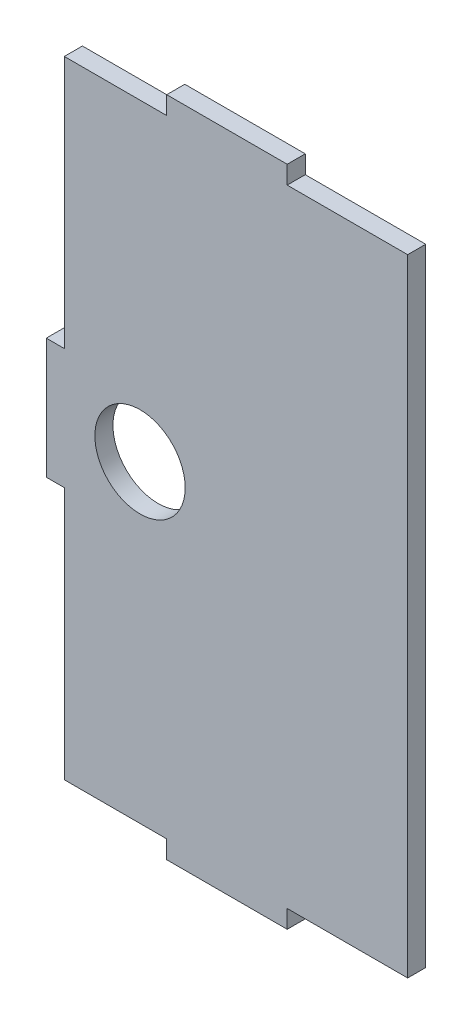
SolidWorks part; units mm, degrees
ref_plane "Front Plane" through (0, 0, 0) normal (0, 0, 1) x (1, 0, 0)
ref_plane "Top Plane" through (0, 0, 0) normal (0, 1, 0) x (1, 0, 0)
ref_plane "Right Plane" through (0, 0, 0) normal (1, 0, 0) x (0, 0, -1)
sketch "Sketch1" plane through (0, 0, 0) normal (0, 0, 1) x (1, 0, 0)
  line L0 (-10, 52) -> (-10, 55)
  line L1 (-27, -52) -> (-10, -52)
  line L3 (-27, 52) -> (-10, 52)
  line L4 (30, -52) -> (30, 52)
  line L5 (-30, -52) -> (30, 52) construction
  line L6 (-30, 52) -> (30, -52) construction
  line L7 (-10, 55) -> (10, 55)
  line L8 (10, 55) -> (10, 52)
  line L9 (-10, -52) -> (-10, -55)
  line L10 (-10, -55) -> (10, -55)
  line L11 (10, -55) -> (10, -52)
  line L12 (10, -55) -> (10.4597, -55.8881)
  line L13 (10, -52) -> (30, -52)
  line L14 (10, 52) -> (30, 52)
  line L15 (-27, 52) -> (-27, -52)
  point P0 (0, 0)
  dimension "D1" = 104
  dimension "D2" = 60
  dimension "D3" = 20
  dimension "D4" = 20
  dimension "D5" = 3
  dimension "D6" = 3
extrude "Boss-Extrude1" add sketch "Sketch1" along normal blind 3 contours L11 L13 L4 L14 L8 L7 L0 L3 L15 L1 L9 L10
sketch "Sketch3" plane through (0, 0, 3) normal (0, 0, 1) x (1, 0, 0)
  circle A0 centre (-14.4329, 0) radius 7.5
  dimension "D1" = 15
extrude "Cut-Extrude1" cut sketch "Sketch3" against normal blind 10
sketch "Sketch4" plane through (-27, 0, 0) normal (-1, 0, 0) x (0, 0, 1)
  line L0 (3, 52) -> (0, 52) construction
  line L1 (0, -10) -> (3, -10)
  line L2 (0, -10) -> (0, 10)
  line L3 (0, 10) -> (3, 10)
  line L4 (3, -10) -> (3, 10)
  line L5 (0, -10) -> (3, 10) construction
  line L6 (0, 10) -> (3, -10) construction
  line L7 (0, -31.35) -> (0, 31.35) construction
  point P0 (1.5, 0)
  dimension "D1" = 3
  dimension "D2" = 20
  dimension "D3" = 52
  dimension "D4" = 1.5
extrude "Boss-Extrude2" add sketch "Sketch4" along normal blind 3
